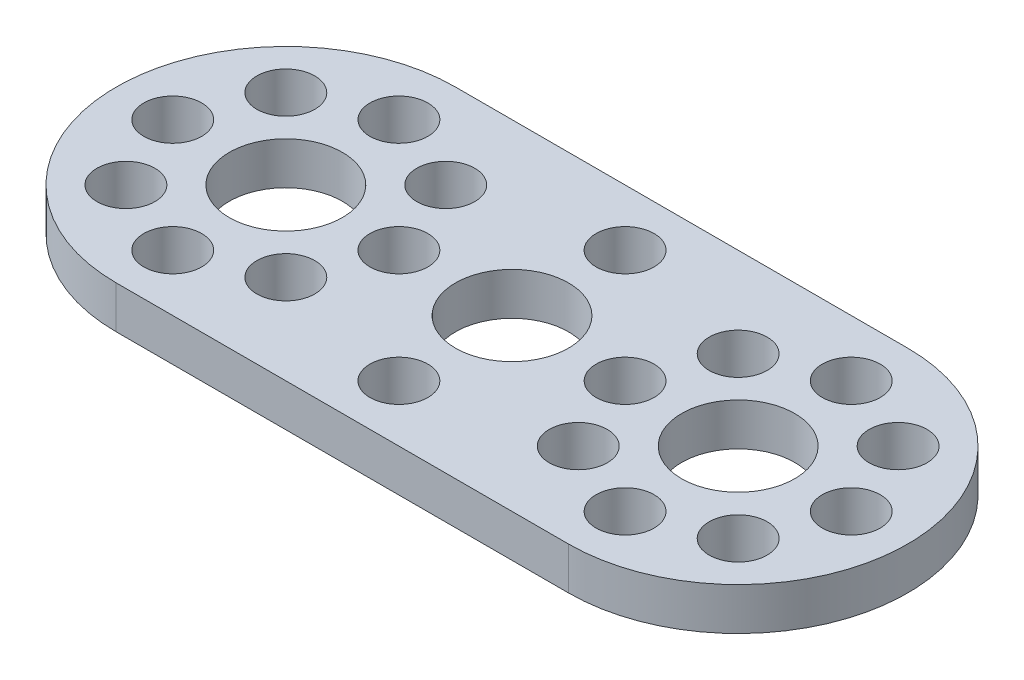
SolidWorks part; units mm, degrees
ref_plane "Front Plane" through (0, 0, 0) normal (0, 0, 1) x (1, 0, 0)
ref_plane "Top Plane" through (0, 0, 0) normal (0, 1, 0) x (1, 0, 0)
ref_plane "Right Plane" through (0, 0, 0) normal (1, 0, 0) x (0, 0, -1)
sketch "Sketch1" plane through (0, 0, 0) normal (0, 1, 0) x (1, 0, 0)
  line L0 (0, 0) -> (32, 0) construction
  line L1 (0, 12) -> (32, 12)
  line L2 (0, -12) -> (32, -12)
  arc A0 (0, 12) -> (0, -12) centre (0, 0) ccw
  arc A1 (32, -12) -> (32, 12) centre (32, 0) ccw
  point P3 (16, 0)
  dimension "D1" = 24
  dimension "D2" = 32
extrude "Boss-Extrude1" add sketch "Sketch1" along normal blind 3
sketch "Sketch2" plane through (0, 3, 0) normal (0, 1, 0) x (1, 0, 0)
  circle A0 centre (0, 0) radius 4
  circle A1 centre (16, 0) radius 4
  circle A2 centre (32, 0) radius 4
  point P7 (0, 0)
  dimension "D1" = 8
  dimension "D2" = 16
  dimension "D3" = 16
extrude "Cut-Extrude1" cut sketch "Sketch2" against normal through all
sketch "Sketch3" plane through (0, 3, 0) normal (0, 1, 0) x (1, 0, 0)
  line L0 (16, 12) -> (16, -12) construction
  line L1 (32, 12) -> (0, 12) construction
  line L2 (0, -12) -> (32, -12) construction
  circle A0 centre (0, 8) radius 2.05
  circle A1 centre (5.6569, 5.6569) radius 2.05
  circle A2 centre (8, 0) radius 2.05
  circle A3 centre (5.6569, -5.6569) radius 2.05
  circle A4 centre (0, -8) radius 2.05
  circle A5 centre (-5.6569, -5.6569) radius 2.05
  circle A6 centre (-8, 0) radius 2.05
  circle A7 centre (-5.6569, 5.6569) radius 2.05
  circle A8 centre (26.3431, -5.6569) radius 2.05
  circle A9 centre (32, -8) radius 2.05
  circle A10 centre (37.6569, -5.6569) radius 2.05
  circle A11 centre (40, 0) radius 2.05
  circle A12 centre (37.6569, 5.6569) radius 2.05
  circle A13 centre (32, 8) radius 2.05
  circle A14 centre (26.3431, 5.6569) radius 2.05
  circle A15 centre (24, 0) radius 2.05
  circle A16 centre (16, 8) radius 2.05
  circle A17 centre (16, -8) radius 2.05
  point P19 (0, 0)
  dimension "D1" = 4.1
  dimension "D4" = 4
  dimension "D2" = 8
  dimension "D5" = 16
  dimension "D6" = 4
  dimension "D3" = 8
extrude "Cut-Extrude2" cut sketch "Sketch3" against normal through all
